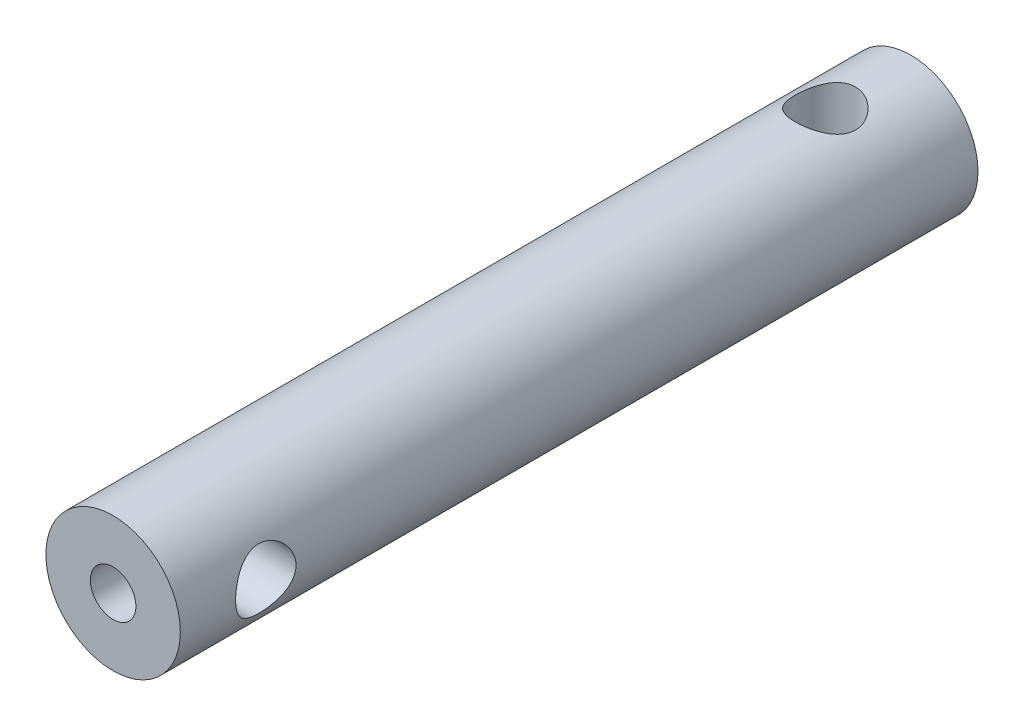
SolidWorks part; units mm, degrees
ref_plane "Front" through (0, 0, 0) normal (0, 0, 1) x (1, 0, 0)
ref_plane "Top" through (0, 0, 0) normal (0, 1, 0) x (1, 0, 0)
ref_plane "Right" through (0, 0, 0) normal (1, 0, 0) x (0, 0, -1)
sketch "Sketch1" plane through (0, 0, 0) normal (0, 0, 1) x (1, 0, 0)
  circle A0 centre (0, 0) radius 7.493
  circle A1 centre (0, 0) radius 2.54
  dimension "D1" = 14.986
  dimension "D2" = 5.08
extrude "Boss-Extrude1" add sketch "Sketch1" along normal blind 88.9
sketch "Sketch7" plane through (0, 0, 0) normal (0, 1, 0) x (1, 0, 0)
  line L1 (2.54, 0) -> (-2.54, 0) construction
  line L3 (7.493, 0) -> (-7.493, 0) construction
  circle A0 centre (0, -9.525) radius 3.3655
  dimension "D1" = 9.525
  dimension "D2" = 9.525
  dimension "D3" = 9.525
  dimension "D4" = 9.525
extrude "Cut-Extrude2" cut sketch "Sketch7" against normal through all both and the other way through all
sketch "Sketch8" plane through (0, 0, 0) normal (1, 0, 0) x (0, 0, -1)
  circle A0 centre (-79.375, 0) radius 3.3655
extrude "Cut-Extrude3" cut sketch "Sketch8" against normal through all both and the other way through all
